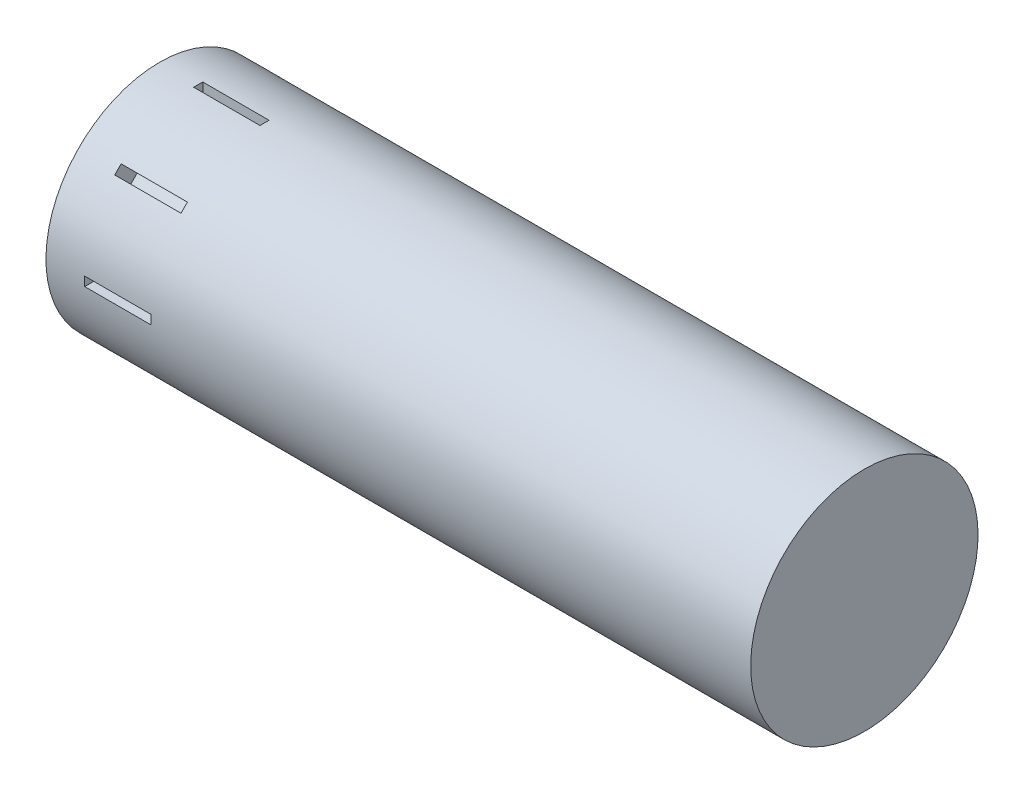
SolidWorks part; units mm, degrees
ref_plane "Ön Düzlem" through (0, 0, 0) normal (0, 0, 1) x (1, 0, 0)
ref_plane "Üst Düzlem" through (0, 0, 0) normal (0, 1, 0) x (1, 0, 0)
ref_plane "Sağ Düzlem" through (0, 0, 0) normal (1, 0, 0) x (0, 0, -1)
sketch "Sketch1" plane through (0, 0, 0) normal (0, 0, 1) x (1, 0, 0)
  line L0 (0, 0) -> (0, 1)
  line L1 (0, 1) -> (-1, 2)
  line L2 (-1, 2) -> (-7, 2)
  line L3 (-7, 2) -> (-7, 4)
  line L4 (-7, 4) -> (-10, 4)
  line L5 (-10, 4) -> (-10, 2)
  line L6 (-10, 2) -> (-16, 2)
  line L7 (-16, 2) -> (-17.5, 3.5)
  line L8 (-17.5, 3.5) -> (-29.5, 3.5)
  line L9 (-29.5, 3.5) -> (-29.5, 5)
  line L10 (-29.5, 5) -> (1.5, 5)
  line L11 (1.5, 5) -> (1.5, 0)
  line L12 (1.5, 0) -> (0, 0)
  dimension "D1" = 1
  dimension "D2" = 135
  dimension "D3" = 1
  dimension "D4" = 2
  dimension "D5" = 3
  dimension "D6" = 6
  dimension "D7" = 1.5
  dimension "D8" = 6
  dimension "D9" = 12
  dimension "D10" = 1.5
  dimension "D11" = 1.5
revolve "Revolve1" add sketch "Sketch1" angle 360 about L12
sketch "Sketch2" plane through (-7, 0, 0) normal (-1, 0, 0) x (0, 0, 1)
  line L0 (-2, 0) -> (-3.9, 0) construction
  line L1 (-2, -0.1) -> (-3.9, -0.1)
  line L2 (-2, 0.1) -> (-3.9, 0.1)
  circle A0 centre (0, 0) radius 2 construction
  circle A1 centre (0, 0) radius 2 construction
  arc A2 (-2, -0.1) -> (-2, 0.1) centre (-2, 0) ccw
  arc A3 (-3.9, 0.1) -> (-3.9, -0.1) centre (-3.9, 0) ccw
  point P8 (-2.95, 0)
  dimension "D1" = 0.1
  dimension "D2" = 1.9
extrude "Cut-Extrude1" cut sketch "Sketch2" against normal blind 0.5 and the other way blind 3.5
pattern_circular "CirPattern1" count 8 over 360 about axis through (0, 0, 0) along (1, 0, 0) of "Cut-Extrude1"
sketch "Sketch3" plane through (0, 0, 0) normal (0, 0, 1) x (1, 0, 0)
  line L0 (-29.5, 5) -> (-29.5, -5) construction
  line L5 (-14.5, 4.5) -> (-13, 3)
  line L6 (-24.8846, 4.5) -> (-14.5, 4.5)
  line L7 (-16, 2.5) -> (-17.5, 4)
  line L9 (-13, 3) -> (-10, 3)
  line L11 (-16, 2.5) -> (-10, 2.5)
  line L12 (-10, 3) -> (-10, 2.5)
  line L14 (-27.8, 4) -> (-27.8, 5.5)
  line L15 (-27.8, 5.5) -> (-24.8846, 5.5)
  line L16 (-24.8846, 4.5) -> (-24.8846, 5.5)
  line L17 (-27.8, 4) -> (-17.5, 4)
  dimension "D2" = 1.5
  dimension "D3" = 0.5
  dimension "D4" = 3
  dimension "D5" = 1.5
  dimension "D6" = 10.3
  dimension "D7" = 6
  dimension "D8" = 1
  dimension "D9" = 1.7
  dimension "D10" = 2.9154
  dimension "D11" = 3
  dimension "D12" = 2
  dimension "D13" = 4
  dimension "D14" = 135
extrude "Cut-Extrude2" cut sketch "Sketch3" against normal blind 0.2 and the other way blind 0.2
pattern_circular "CirPattern2" count 8 over 360 about axis through (0, 0, 0) along (1, 0, 0) of "Cut-Extrude2"
